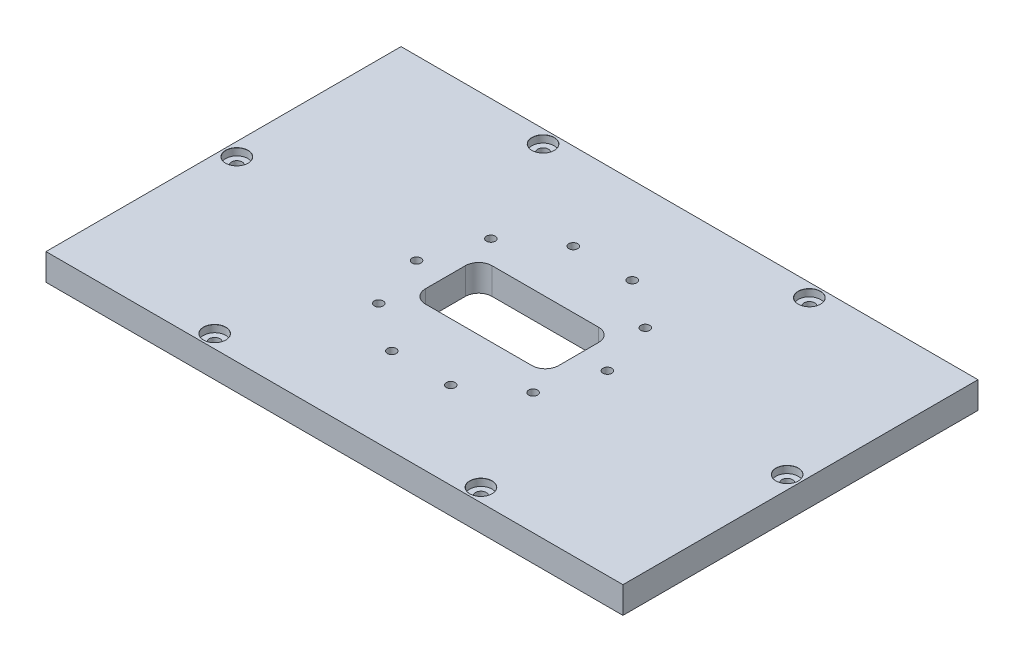
SolidWorks part; units mm, degrees
ref_plane "Ebene vorne" through (0, 0, 0) normal (0, 0, 1) x (1, 0, 0)
ref_plane "Ebene oben" through (0, 0, 0) normal (0, 1, 0) x (1, 0, 0)
ref_plane "Ebene rechts" through (0, 0, 0) normal (1, 0, 0) x (0, 0, -1)
sketch "Skizze1" plane through (0, 0, 0) normal (0, 1, 0) x (1, 0, 0)
  line L1 (0, 0) -> (130, 0)
  line L2 (0, 0) -> (0, 80)
  line L3 (0, 80) -> (130, 80)
  line L4 (130, 0) -> (130, 80)
  dimension "D1" = 80
  dimension "D2" = 130
extrude "Aufsatz-Linear austragen1" add sketch "Skizze1" along normal blind 6
hole_wizard "Ø2.4 (2.4) Durchmesser Bohrung1" positions "Skizze2" profile "Skizze3" hole size "Ø2.4" standard "DIN"
sketch "Skizze2" plane through (0, 6, 0) normal (0, 1, 0) x (1, 0, 0)
  line L0 (130, 80) -> (0, 80) construction
  line L1 (130, 0) -> (130, 80) construction
  line L2 (0, -3.3) -> (0, 3.3) construction
  line L3 (-3.3, 0) -> (3.3, 0) construction
  point P0 (35, 77)
  point P2 (95, 77)
  point P4 (127, 40)
  point P6 (95, 3)
  point P8 (35, 3)
  point P10 (3, 40)
  point P21 (133.0887, 32.8034)
  dimension "D1" = 3
  dimension "D2" = 3
  dimension "D3" = 3
  dimension "D4" = 3
  dimension "D5" = 3
  dimension "D6" = 3
  dimension "D7" = 35
  dimension "D8" = 35
  dimension "D9" = 35
  dimension "D10" = 35
  dimension "D11" = 40
  dimension "D12" = 40
sketch "Skizze3" plane through (35, 6, -77) normal (1, 0, 0) x (0, 0, 1)
  line L0 (0, 0) -> (0, 10.721)
  line L1 (0, 10.721) -> (1.2, 10)
  line L2 (1.2, 10) -> (1.2, 0.025)
  line L3 (1.2, 0.025) -> (1.225, 0)
  line L5 (1.225, 0) -> (0, 0)
  line L6 (-1.2, 0.025) -> (-1.225, 0) construction
  line L10 (0, 10.721) -> (-1.2, 10) construction
  line L11 (0, -6.35) -> (0, 107.95) construction
  dimension "Bohrerdurchmesser" = 2.4
  dimension "Bohrungstiefe" = 10
  dimension "Senkdurchmesser2 (Oben)" = 2.45
  dimension "Senkwinkel2 (Oben)" = 90
  dimension "Spitzenwinkel" = 118
hole_wizard "Stirnsenkung für M2 Flachkopfschraube mit Schlitz1" positions "Skizze6" profile "Skizze7" counterbore size "M2" standard "DIN"
sketch "Skizze6" plane through (0, 6, 0) normal (0, 1, 0) x (1, 0, 0)
  point P0 (95, 3)
  point P3 (127, 40)
  point P6 (95, 77)
  point P9 (35, 77)
  point P12 (3, 40)
  point P15 (35, 3)
sketch "Skizze7" plane through (95, 6, -3) normal (1, 0, 0) x (0, 0, 1)
  line L0 (0, 0) -> (0, 2.721)
  line L1 (0, 2.721) -> (1.2, 2)
  line L2 (1.2, 2) -> (1.2, 1.6)
  line L3 (1.2, 1.6) -> (2.5, 1.6)
  line L5 (2.5, 1.6) -> (2.5, 0.025)
  line L6 (2.5, 0.025) -> (2.525, 0)
  line L7 (2.525, 0) -> (0, 0)
  line L8 (-2.5, 0.025) -> (-2.525, 0) construction
  line L10 (0, 2.721) -> (-1.2, 2) construction
  line L11 (0, -6.35) -> (0, 107.95) construction
  dimension "Bohrerdurchmesser" = 2.4
  dimension "Bohrungstiefe" = 2
  dimension "Senkdurchmesser2" = 5
  dimension "Senktiefe2" = 1.6
  dimension "Senkdurchmesser4 (Oben)" = 5.05
  dimension "Senkwinkel2 (Oben)" = 90
  dimension "Spitzenwinkel" = 118
sketch "Skizze8" plane through (0, 6, 0) normal (0, 1, 0) x (1, 0, 0)
  line L0 (65, -24.4296) -> (65, 94.5281) construction
  line L1 (130, 0) -> (130, 80) construction
  line L3 (0, 80) -> (0, 0) construction
  line L4 (147.1504, 40) -> (-23.042, 40) construction
  line L5 (0, 0) -> (130, 0) construction
  line L6 (130, 80) -> (0, 80) construction
  line L11 (80, 32.5) -> (50, 32.5)
  line L12 (80, 32.5) -> (80, 47.5)
  line L13 (80, 47.5) -> (50, 47.5)
  line L14 (50, 32.5) -> (50, 47.5)
  circle A1 centre (47.6061, 52.6374) radius 1
  circle A2 centre (58.3561, 60.4477) radius 1
  circle A3 centre (71.6439, 60.4477) radius 1
  circle A4 centre (82.3939, 52.6374) radius 1
  circle A5 centre (86.5, 40) radius 1
  circle A6 centre (82.3939, 27.3626) radius 1
  circle A7 centre (71.6439, 19.5523) radius 1
  circle A8 centre (58.3561, 19.5523) radius 1
  circle A9 centre (47.6061, 27.3626) radius 1
  circle A10 centre (43.5, 40) radius 1
  point P14 (65, 40)
  dimension "D1" = 2
  dimension "D3" = 43
  dimension "D11" = 30
  dimension "D12" = 15
  dimension "D2" = 10
extrude "Schnitt-Linear austragen1" cut sketch "Skizze8" against normal up to surface (6 mm away) up to face at (35, 0, -78.2)
fillet "Verrundung1" radius 3 4 edges at (80, 3, -47.5) (50, 3, -47.5) (50, 3, -32.5) (80, 3, -32.5)
